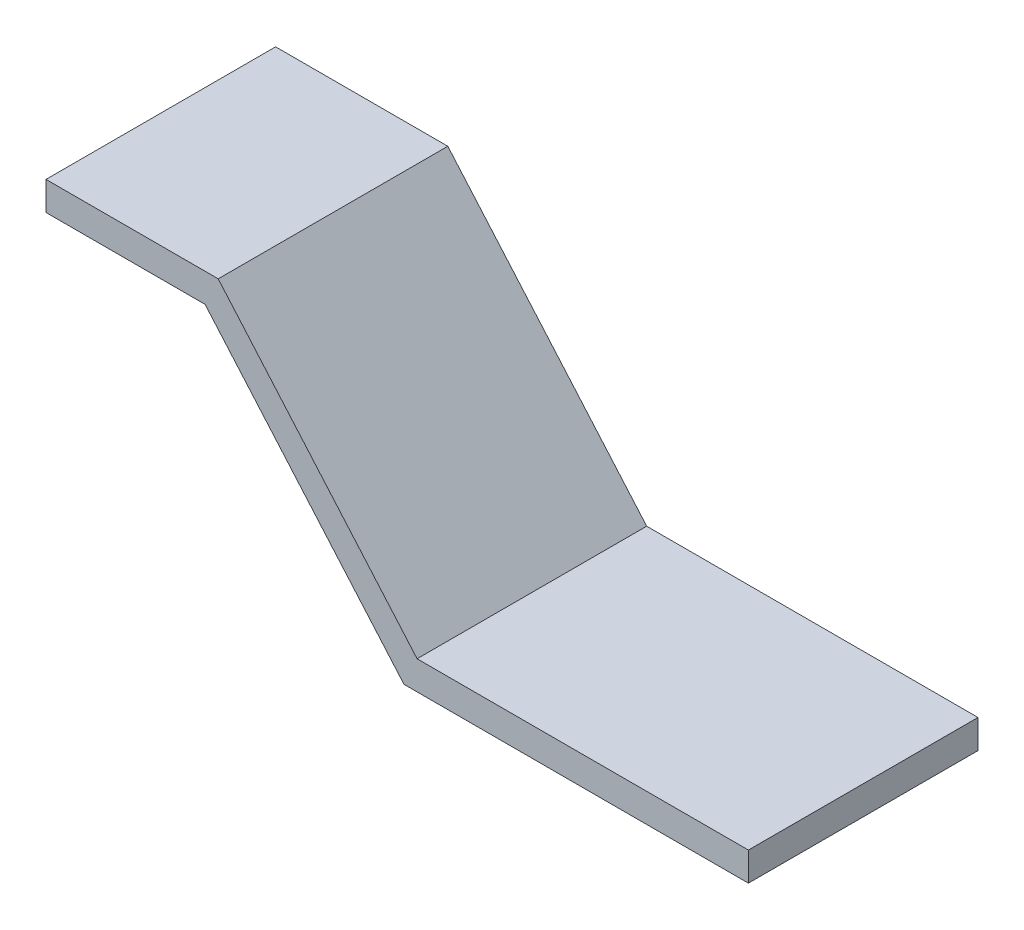
SolidWorks part; units mm, degrees
material "1060 Alloy"
ref_plane "Front Plane" through (0, 0, 0) normal (0, 0, 1) x (1, 0, 0)
ref_plane "Top Plane" through (0, 0, 0) normal (0, 1, 0) x (1, 0, 0)
ref_plane "Right Plane" through (0, 0, 0) normal (1, 0, 0) x (0, 0, -1)
sketch "Sketch2" plane through (0, 0, 0) normal (0, 0, 1) x (1, 0, 0)
  line L0 (0, 0) -> (150, 0)
  line L1 (150, 0) -> (323.2219, -200)
  line L2 (323.2219, -200) -> (611.8014, -200)
  line L3 (611.8014, -200) -> (611.8014, -225)
  line L4 (611.8014, -225) -> (311.8014, -225)
  line L5 (311.8014, -225) -> (138.5795, -25)
  line L6 (138.5795, -25) -> (0, -25)
  line L7 (0, -25) -> (0, 0)
  dimension "D1" = 25
  dimension "D2" = 25
  dimension "D3" = 25
  dimension "D4" = 300
  dimension "D5" = 150
extrude "Boss-Extrude2" add sketch "Sketch2" along normal blind 200
